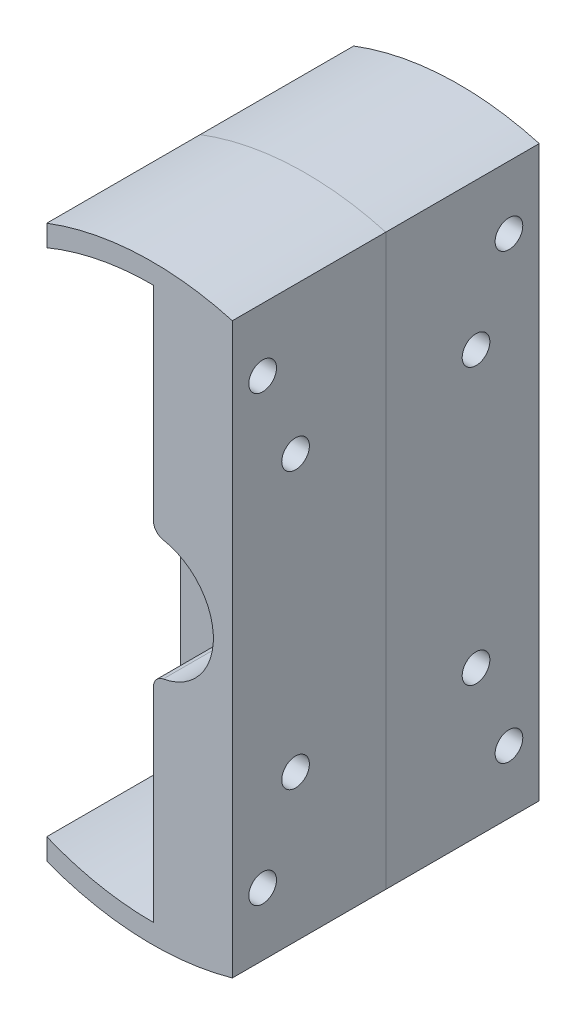
SolidWorks part; units mm, degrees
ref_plane "Front Plane" through (0, 0, 0) normal (0, 0, 1) x (1, 0, 0)
ref_plane "Top Plane" through (0, 0, 0) normal (0, 1, 0) x (1, 0, 0)
ref_plane "Right Plane" through (0, 0, 0) normal (1, 0, 0) x (0, 0, -1)
other "Configuration Table"
sketch "草图2" plane through (0, 0, 0) normal (0, 0, 1) x (-1, 0, 0)
  line L0 (0, 41.5) -> (-0.2, 41.5) construction
  line L1 (-0.2, 41.5) -> (-0.2, 10.9183)
  line L2 (-0.2, -41.5) -> (-0.2, -10.9183)
  line L3 (-0.2, 41.5) -> (-0.2, 41.8995)
  line L4 (-0.2, -41.5) -> (-0.2, -41.8995)
  line L5 (-12.1813, -43.216) -> (-12.1813, 43.216)
  line L6 (16, -41.9525) -> (16, -38.7248)
  line L7 (16, 38.7248) -> (16, 41.9525)
  arc A0 (-1.6757, 9.1478) -> (-1.6757, -9.1478) centre (0, 0) ccw
  arc A1 (16, 38.7248) -> (-0.2, 41.8995) centre (0, 0) ccw
  arc A3 (-1.6757, 9.1478) -> (-0.2, 10.9183) centre (-2, 10.9183) ccw
  arc A4 (-0.2, -10.9183) -> (-1.6757, -9.1478) centre (-2, -10.9183) ccw
  arc A5 (16, 41.9525) -> (-12.1813, 43.216) centre (0, 0) ccw
  arc A6 (-0.2, -41.8995) -> (16, -38.7248) centre (0, 0) ccw
  arc A7 (-12.1813, -43.216) -> (16, -41.9525) centre (0, 0) ccw
  point P22 (-12.1813, 0)
  point P27 (16, 0)
  dimension "D1" = 3
extrude "凸台-拉伸1" add sketch "草图2" against normal blind 20.3 contours L7 A5 L5 A7 L6 A6 L4 L2 A4 A0 A3 L1 L3 A1
sketch "草图5" plane through (0.2, 0, 0) normal (-1, 0, 0) x (0, 0, 1)
  line L3 (-20, 41.5) -> (-20, 10.9183) construction
  line L5 (-20, -10.9183) -> (-20, -41.5) construction
  circle A4 centre (-4.6, 33.6671) radius 2.1
  circle A5 centre (-9.6, 20.9183) radius 2.1
  circle A6 centre (-9.6, -20.9183) radius 2.1
  circle A7 centre (-4.6, -33.6671) radius 2.1
  dimension "D1" = 15.4
  dimension "D2" = 10.4
  dimension "D3" = 10.4
  dimension "D4" = 15.4
extrude "切除-拉伸1" cut sketch "草图5" against normal through all
sketch "草图7" plane through (0, 0, -20.3) normal (0, 0, -1) x (-1, 0, 0)
  line L0 (-12.1813, 43.216) -> (-12.1813, -43.216)
  line L1 (16, 41.9525) -> (16, -41.9525)
  arc A0 (-12.1813, -43.216) -> (16, -41.9525) centre (0, 0) ccw
  arc A1 (-12.1813, 43.216) -> (16, 41.9525) centre (0, 0) cw
extrude "凸台-拉伸2" add sketch "草图7" along normal blind 3
mirror "镜向2" about plane through (0, 0, -23.3) normal (0, 0, 1) of bodies 108
